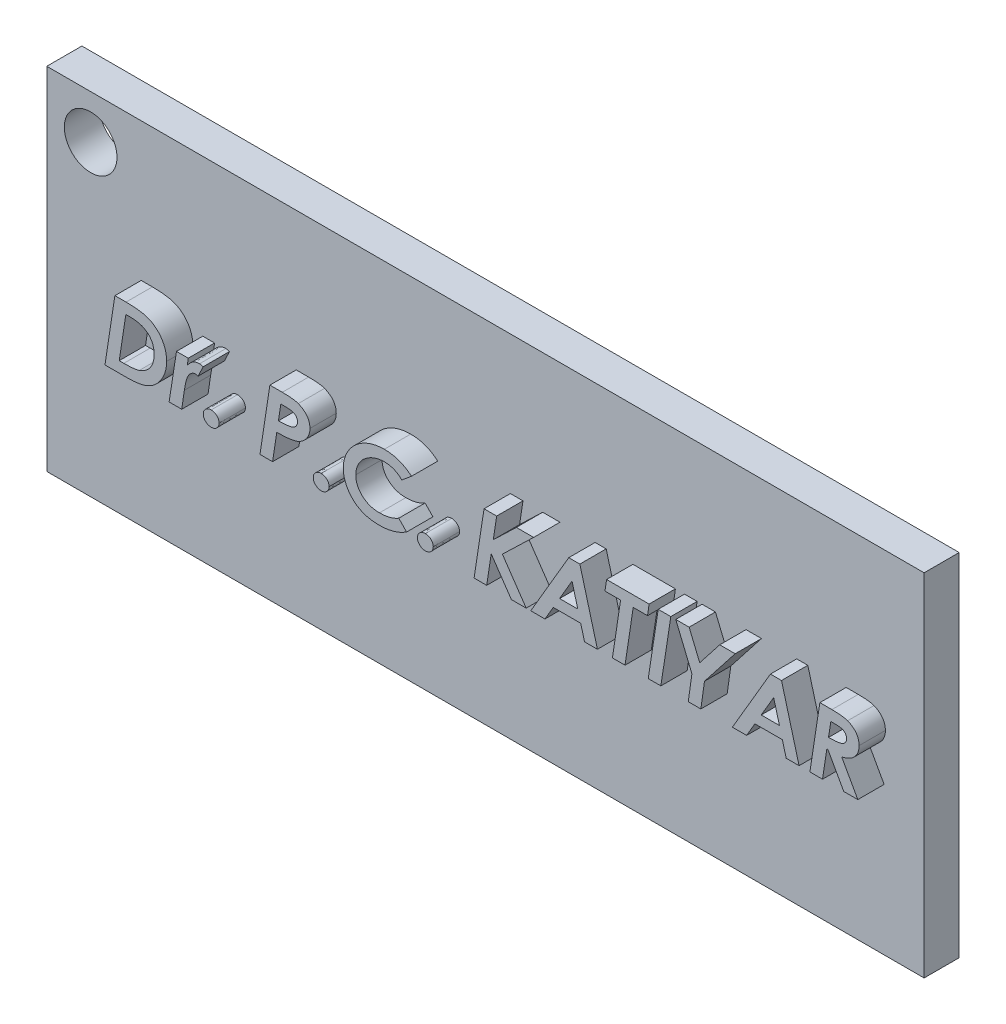
SolidWorks part; units mm, degrees
ref_plane "Front Plane" through (0, 0, 0) normal (0, 0, 1) x (1, 0, 0)
ref_plane "Top Plane" through (0, 0, 0) normal (0, 1, 0) x (1, 0, 0)
ref_plane "Right Plane" through (0, 0, 0) normal (1, 0, 0) x (0, 0, -1)
sketch "Sketch1" plane through (0, 0, 0) normal (0, 0, 1) x (1, 0, 0)
  line L1 (-25, -10) -> (25, -10)
  line L2 (-25, -10) -> (-25, 10)
  line L3 (-25, 10) -> (25, 10)
  line L4 (25, -10) -> (25, 10)
  line L5 (-25, -10) -> (25, 10) construction
  line L6 (-25, 10) -> (25, -10) construction
  point P0 (0, 0)
  dimension "D1" = 20
  dimension "D2" = 50
extrude "Boss-Extrude1" add sketch "Sketch1" along normal blind 2
sketch "Sketch2" plane through (0, 0, 2) normal (0, 0, 1) x (1, 0, 0)
  line L0 (-25, 10) -> (-25, -10) construction
  line L1 (25, 10) -> (-25, 10) construction
  circle A0 centre (-22.5, 7.5) radius 1.5
  dimension "D1" = 3
  dimension "D2" = 2.5
  dimension "D3" = 2.5
extrude "Cut-Extrude1" cut sketch "Sketch2" against normal blind 2
sketch "Sketch3" plane through (0, 0, 2) normal (0, 0, 1) x (1, 0, 0)
  text T0 "Dr. P.C. KATIYAR" font "Century Gothic" height in points 14
extrude "Boss-Extrude2" add sketch "Sketch3" along normal blind 1.5
